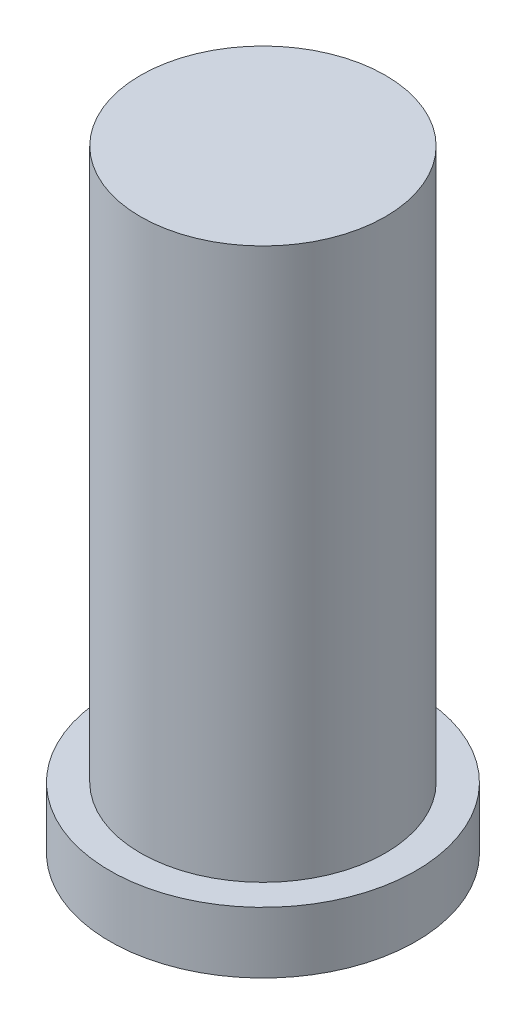
SolidWorks part; units mm, degrees
ref_plane "Front Plane" through (0, 0, 0) normal (0, 0, 1) x (1, 0, 0)
ref_plane "Top Plane" through (0, 0, 0) normal (0, 1, 0) x (1, 0, 0)
ref_plane "Right Plane" through (0, 0, 0) normal (1, 0, 0) x (0, 0, -1)
sketch "Sketch1" plane through (0, 0, 0) normal (0, 1, 0) x (1, 0, 0)
  circle A0 centre (0, 0) radius 4
  dimension "D1" = 8
extrude "Boss-Extrude1" add sketch "Sketch1" along normal blind 18
sketch "Sketch2" plane through (0, 0, 0) normal (0, -1, 0) x (-1, 0, 0)
  circle A0 centre (0, 0) radius 5
  dimension "D1" = 10
extrude "Boss-Extrude2" add sketch "Sketch2" along normal blind 2
